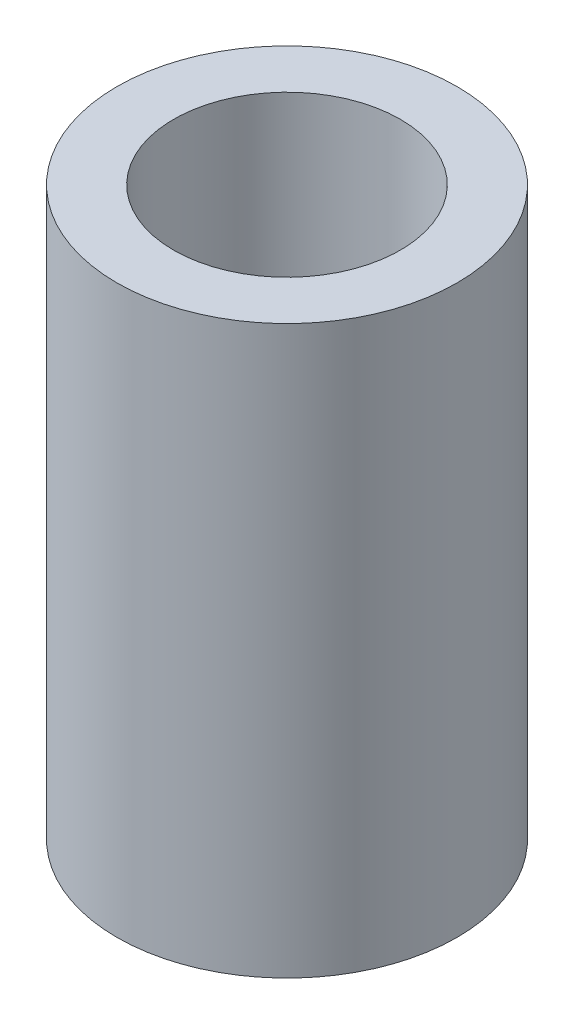
SolidWorks part; units mm, degrees
ref_plane "前视基准面" through (0, 0, 0) normal (0, 0, 1) x (1, 0, 0)
ref_plane "上视基准面" through (0, 0, 0) normal (0, 1, 0) x (1, 0, 0)
ref_plane "右视基准面" through (0, 0, 0) normal (1, 0, 0) x (0, 0, -1)
other "Configuration Table"
sketch "草图1" plane through (0, 0, 0) normal (0, 1, 0) x (1, 0, 0)
  circle A0 centre (0, 0) radius 3
  circle A1 centre (0, 0) radius 2
  dimension "D1" = 4
  dimension "D2" = 6
extrude "凸台-拉伸1" add sketch "草图1" along normal blind 10
